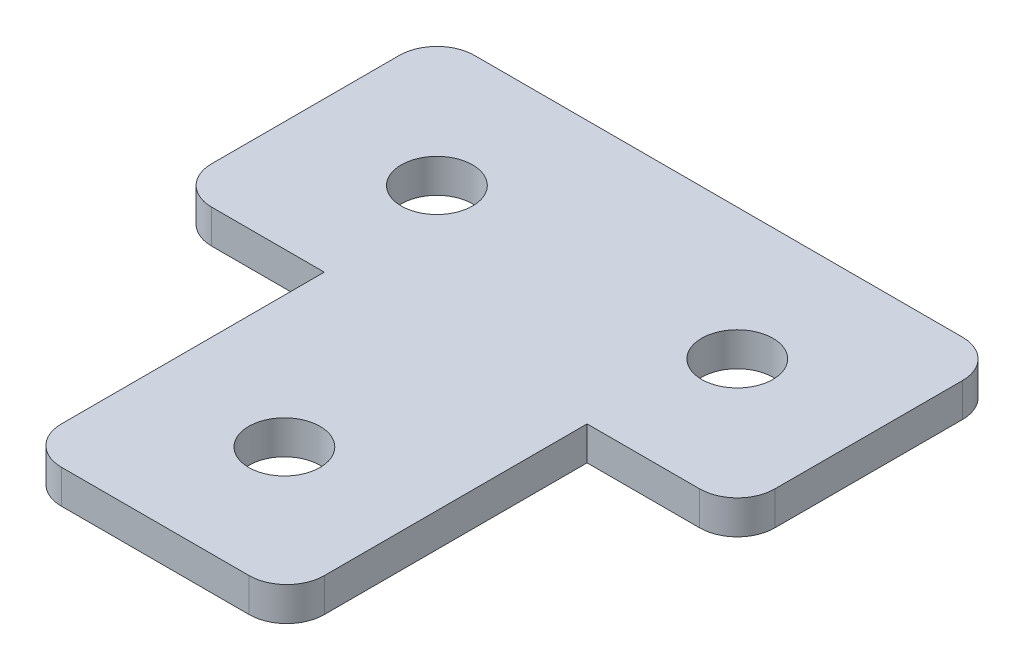
SolidWorks part; units mm, degrees
ref_plane "前视基准面" through (0, 0, 0) normal (0, 0, 1) x (1, 0, 0)
ref_plane "上视基准面" through (0, 0, 0) normal (0, 1, 0) x (1, 0, 0)
ref_plane "右视基准面" through (0, 0, 0) normal (1, 0, 0) x (0, 0, -1)
other "Configuration Table"
sketch "草图1" plane through (0, 0, 0) normal (0, 1, 0) x (1, 0, 0)
  line L0 (0, -14) -> (8, -14)
  line L1 (0, 0) -> (30, 0)
  line L2 (0, 0) -> (0, -14)
  line L3 (8, -30) -> (22, -30)
  line L4 (30, 0) -> (30, -14)
  line L5 (8, -14) -> (8, -30)
  line L6 (22, -14) -> (22, -30)
  line L7 (22, -14) -> (30, -14)
  line L8 (-2.5742, -7) -> (35.3335, -7) construction
  line L9 (15, -33.2831) -> (15, 6.1036) construction
  circle A0 centre (7, -7) radius 1.9
  circle A1 centre (23, -7) radius 1.9
  circle A2 centre (15, -23.1245) radius 1.9
  point P19 (0, 0)
  dimension "D2" = 3.8
  dimension "D6" = 3.8
  dimension "D7" = 3.8
  dimension "D1" = 30
  dimension "D3" = 16
  dimension "D4" = 8
  dimension "D5" = 8
  dimension "D8" = 16
  dimension "D9" = 8
  dimension "D10" = 18
  dimension "D11" = 7
extrude "凸台-拉伸1" add sketch "草图1" along normal blind 1.8
fillet "圆角1" radius 2 6 edges at (0, 0.9, 14) (30, 0.9, 0) (30, 0.9, 14) (8, 0.9, 30) (22, 0.9, 30) (0, 0.9, 0)
